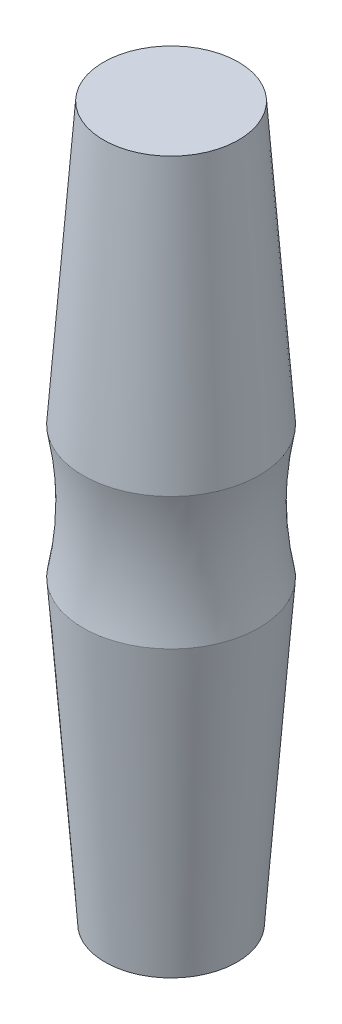
SolidWorks part; units mm, degrees
ref_plane "Front Plane" through (0, 0, 0) normal (0, 0, 1) x (1, 0, 0)
ref_plane "Top Plane" through (0, 0, 0) normal (0, 1, 0) x (1, 0, 0)
ref_plane "Right Plane" through (0, 0, 0) normal (1, 0, 0) x (0, 0, -1)
sketch "Sketch1" plane through (0, 0, 0) normal (0, 0, 1) x (1, 0, 0)
  line L0 (0, -44.0138) -> (0, 37.4039) construction
  line L1 (0, 31.47) -> (6.1347, 31.47)
  line L2 (6.1347, 31.47) -> (8, 6)
  line L3 (8, 6) -> (8, -6) construction
  line L4 (8, -6) -> (6, -33.31)
  line L5 (6, -33.31) -> (0, -33.31)
  line L6 (0, 0) -> (72.2545, 0) construction
  line L7 (0, 31.47) -> (0, -33.31)
  line L8 (6, -33.31) -> (6, 0) construction
  arc A0 (8, 6) -> (8, -6) centre (38, 0) ccw
  point P7 (72.2545, 0)
  point P9 (8, 0)
  dimension "D2" = 8
  dimension "D4" = 31.47
  dimension "D5" = 12
  dimension "D8" = 30
  dimension "D1" = 6
  dimension "D6" = 175.812
  dimension "D7" = 175.812
  dimension "D3" = 33.31
revolve "Revolve1" add sketch "Sketch1" angle 360 about L0
equation "\"D4@Sketch1\"=31.47"
equation "\"D7@Sketch1\"=\"D6@Sketch1\""
